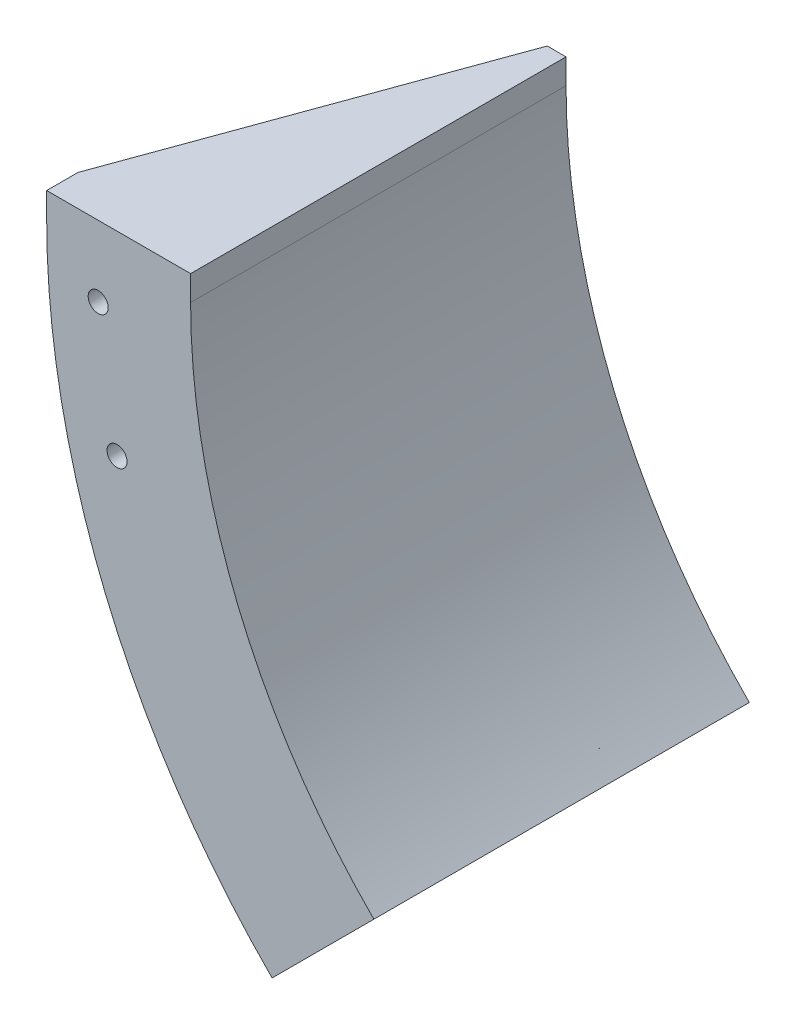
SolidWorks part; units mm, degrees
material "打印件"
ref_plane "前视基准面" through (0, 0, 0) normal (0, 0, 1) x (1, 0, 0)
ref_plane "上视基准面" through (0, 0, 0) normal (0, 1, 0) x (1, 0, 0)
ref_plane "右视基准面" through (0, 0, 0) normal (1, 0, 0) x (0, 0, -1)
sketch "草图1" plane through (0, 0, 0) normal (0, 0, 1) x (1, 0, 0)
  line L2 (-100, 0) -> (-103, 0)
  line L3 (-70.7107, -70.7107) -> (-72.832, -72.832)
  arc A2 (-100, 0) -> (-70.7107, -70.7107) centre (0, 0) ccw
  arc A3 (-103, 0) -> (-72.832, -72.832) centre (0, 0) ccw
  dimension "D1" = 200
  dimension "D2" = 206
  dimension "D3" = 45
extrude "凸台-拉伸1" add sketch "草图1" along normal blind 60
sketch "草图2" plane through (0, 0, 60) normal (0, 0, 1) x (1, 0, 0)
  line L2 (-103, 0) -> (-123, 0)
  line L5 (-72.832, -72.832) -> (-86.9741, -86.9741)
  arc A4 (-123, 0) -> (-86.9741, -86.9741) centre (0, 0) ccw
  arc A5 (-103, 0) -> (-72.832, -72.832) centre (0, 0) ccw construction
  arc A6 (-103, 0) -> (-72.832, -72.832) centre (0, 0) ccw
  dimension "D1" = 246
extrude "凸台-拉伸2" add sketch "草图2" against normal blind 5
sketch "草图4" plane through (0, 0, 55) normal (0, 0, -1) x (-1, 0, 0)
  line L0 (111.7546, -27.1275) -> (0, 0) construction
  line L1 (0, 0) -> (114.7675, -7.3094) construction
  circle A0 centre (111.7546, -27.1275) radius 1.6
  circle A1 centre (114.7675, -7.3094) radius 1.6
  circle A2 centre (0, 0) radius 115 construction
  dimension "D1" = 3.2
  dimension "D2" = 3.2
  dimension "D3" = 10
  dimension "D4" = 230
extrude "切除-拉伸1" cut sketch "草图4" against normal through all
sketch "草图6" plane through (0, 0, 0) normal (0.7071, -0.7071, 0) x (0, 0, -1)
  line L0 (-55, -123) -> (-55, -103)
  line L2 (0, -103) -> (0, -72.832) construction
  line L3 (-55, -103) -> (0, -103) construction
  line L4 (0, -103) -> (-55, -123)
  line L5 (0, -103) -> (0, -100)
  line L6 (0, -100) -> (-55, -100)
  line L7 (-60, -100) -> (0, -100) construction
  line L8 (-55, -100) -> (-55, -103)
extrude "凸台-拉伸3" add sketch "草图6" against normal blind 4 separate body
sketch "草图7" plane through (0, 0, 0) normal (0, 1, 0) x (1, 0, 0)
  line L0 (-103, 0) -> (-123, -55)
  line L1 (-123, -55) -> (-123, -60)
  line L2 (-123, -60) -> (-100, -60)
  line L3 (-100, -60) -> (-100, 0)
  line L4 (-100, -60) -> (-100, 0) construction
  line L5 (-100, 0) -> (-103, 0)
extrude "凸台-拉伸4" add sketch "草图7" along normal blind 4
